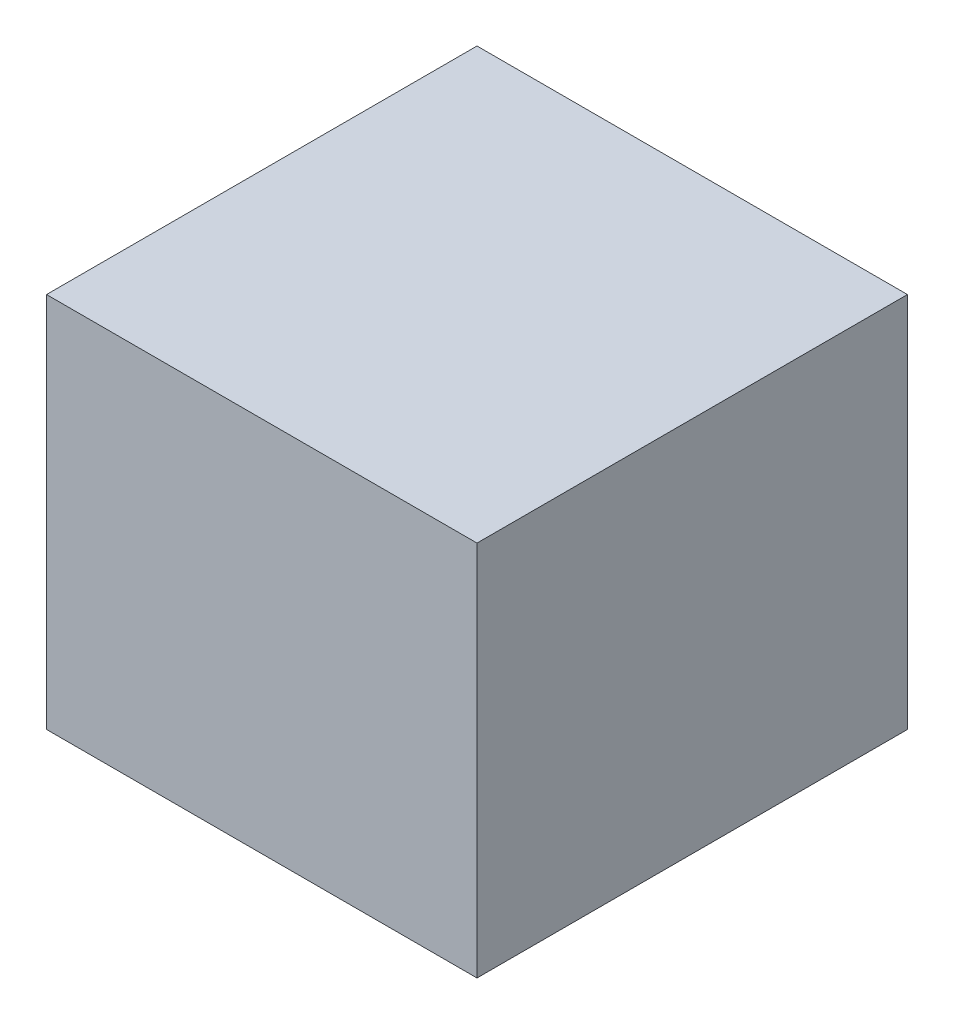
SolidWorks part; units mm, degrees
material "1023 Carbon Steel Sheet (SS)"
ref_plane "Front Plane" through (0, 0, 0) normal (0, 0, 1) x (1, 0, 0)
ref_plane "Top Plane" through (0, 0, 0) normal (0, 1, 0) x (1, 0, 0)
ref_plane "Right Plane" through (0, 0, 0) normal (1, 0, 0) x (0, 0, -1)
sketch "Sketch1" plane through (0, 0, 0) normal (0, 0, 1) x (1, 0, 0)
  line L1 (0, 0) -> (400, 0)
  line L2 (0, 0) -> (0, 350)
  line L3 (0, 350) -> (400, 350)
  line L4 (400, 0) -> (400, 350)
  dimension "D1" = 400
  dimension "D2" = 350
extrude "Boss-Extrude1" add sketch "Sketch1" along normal blind 400
